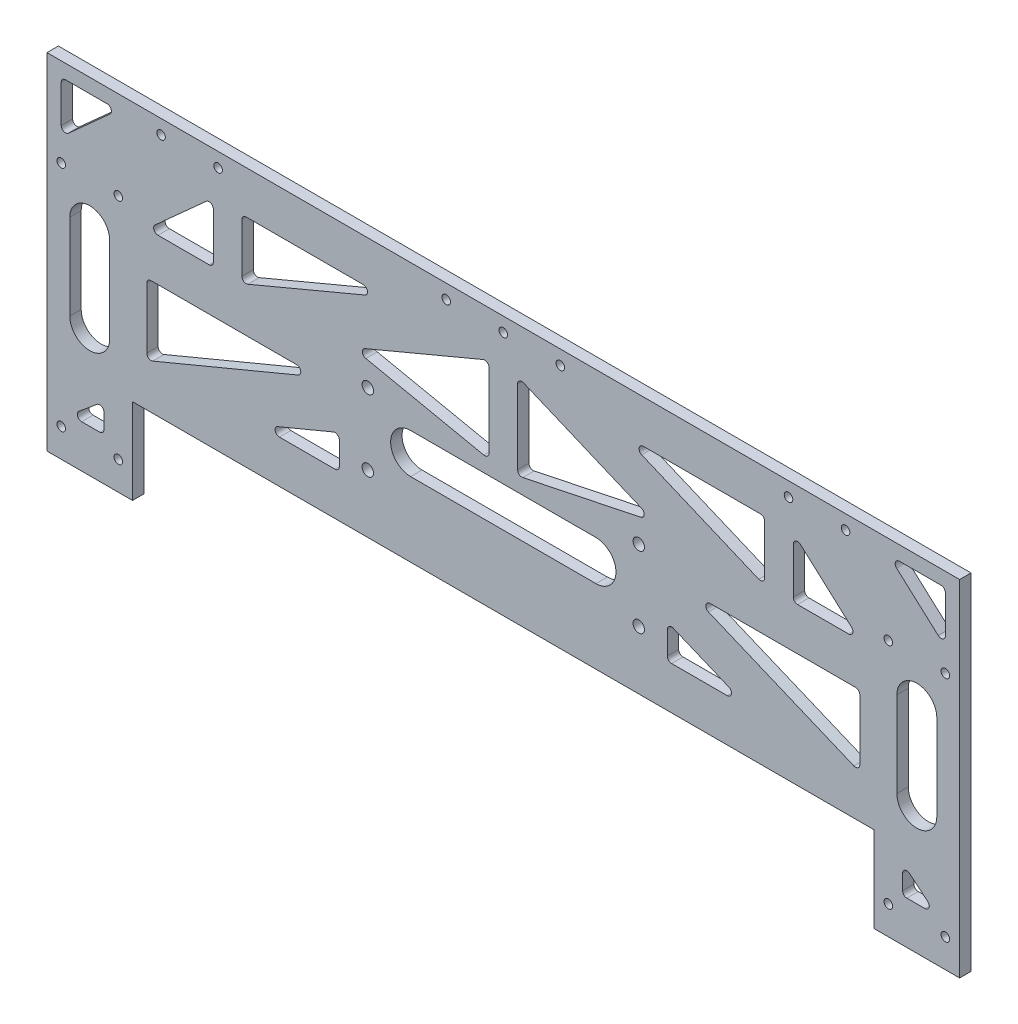
SolidWorks part; units mm, degrees
material "Thornel Mat VMA"
ref_plane "前视基准面" through (0, 0, 0) normal (0, 0, 1) x (1, 0, 0)
ref_plane "上视基准面" through (0, 0, 0) normal (0, 1, 0) x (1, 0, 0)
ref_plane "右视基准面" through (0, 0, 0) normal (1, 0, 0) x (0, 0, -1)
sketch "草图1" plane through (0, 0, 0) normal (0, 0, 1) x (1, 0, 0)
  line L1 (0, 0) -> (320, 0)
  line L2 (0, 0) -> (0, 121)
  line L3 (0, 121) -> (320, 121)
  line L4 (320, 0) -> (320, 121)
  dimension "D1" = 320
  dimension "D2" = 121
extrude "凸台-拉伸1" add sketch "草图1" along normal blind 4
sketch "草图2" plane through (0, 0, 4) normal (0, 0, 1) x (1, 0, 0)
  line L0 (160, 121) -> (160, 0) construction
  line L1 (320, 121) -> (0, 121) construction
  line L2 (0, 0) -> (320, 0) construction
  line L3 (0, 121) -> (0, 0) construction
  line L4 (30, 0) -> (35, 0)
  line L5 (30, 0) -> (30, 30)
  line L6 (30, 30) -> (35, 30)
  line L7 (35, 0) -> (35, 30)
  line L8 (285, 0) -> (285, 30)
  line L9 (290, 30) -> (285, 30)
  line L10 (290, 0) -> (290, 30)
  line L11 (290, 0) -> (285, 0)
  dimension "D1" = 30
  dimension "D2" = 30
  dimension "D3" = 5
extrude "切除-拉伸1" cut sketch "草图2" against normal through all
sketch "草图3" plane through (0, 0, 4) normal (0, 0, 1) x (1, 0, 0)
  line L0 (40, 116) -> (60, 116) construction
  line L1 (160, 121) -> (160, 0) construction
  line L2 (320, 121) -> (0, 121) construction
  line L3 (35, 0) -> (285, 0) construction
  line L4 (140, 116) -> (160, 116) construction
  line L5 (0, 121) -> (0, 0) construction
  line L6 (280, 116) -> (260, 116) construction
  circle A0 centre (40, 116) radius 1.5
  circle A1 centre (60, 116) radius 1.5
  circle A2 centre (140, 116) radius 1.5
  circle A3 centre (160, 116) radius 1.5
  circle A4 centre (260, 116) radius 1.5
  circle A5 centre (280, 116) radius 1.5
  circle A6 centre (180, 116) radius 1.5
  dimension "D5" = 3
  dimension "D1" = 40
  dimension "D2" = 5
  dimension "D3" = 20
  dimension "D4" = 20
extrude "切除-拉伸2" cut sketch "草图3" against normal through all
sketch "草图4" plane through (0, 0, 4) normal (0, 0, 1) x (1, 0, 0)
  line L0 (160, 121) -> (160, 0) construction
  line L1 (5, 90) -> (25, 90) construction
  line L2 (5, 90) -> (5, 10) construction
  line L3 (5, 10) -> (25, 10) construction
  line L4 (25, 90) -> (25, 10) construction
  line L5 (320, 121) -> (0, 121) construction
  line L6 (35, 0) -> (285, 0) construction
  line L7 (0, 0) -> (30, 0) construction
  line L8 (0, 121) -> (0, 0) construction
  line L10 (295, 90) -> (295, 10) construction
  line L11 (315, 10) -> (295, 10) construction
  line L12 (315, 90) -> (315, 10) construction
  line L13 (315, 90) -> (295, 90) construction
  circle A0 centre (5, 90) radius 1.5
  circle A1 centre (25, 90) radius 1.5
  circle A2 centre (5, 10) radius 1.5
  circle A3 centre (25, 10) radius 1.5
  circle A4 centre (295, 10) radius 1.5
  circle A5 centre (315, 10) radius 1.5
  circle A6 centre (295, 90) radius 1.5
  circle A7 centre (315, 90) radius 1.5
  dimension "D5" = 3
  dimension "D1" = 10
  dimension "D2" = 80
  dimension "D3" = 5
  dimension "D4" = 20
extrude "切除-拉伸3" cut sketch "草图4" against normal through all
sketch "草图6" plane through (0, 0, 4) normal (0, 0, 1) x (1, 0, 0)
  line L0 (160, 121) -> (160, 0) construction
  line L1 (320, 121) -> (0, 121) construction
  line L2 (35, 0) -> (285, 0) construction
  line L3 (127.5, 63) -> (192.5, 63) construction
  line L4 (112.5, 50.5) -> (207.5, 50.5) construction
  line L5 (112.5, 50.5) -> (112.5, 75.5) construction
  line L6 (112.5, 75.5) -> (207.5, 75.5) construction
  line L7 (207.5, 50.5) -> (207.5, 75.5) construction
  line L8 (112.5, 50.5) -> (207.5, 75.5) construction
  line L9 (112.5, 75.5) -> (207.5, 50.5) construction
  line L10 (127.5, 70) -> (192.5, 70)
  line L11 (127.5, 56) -> (192.5, 56)
  circle A0 centre (112.5, 75.5) radius 2
  circle A1 centre (207.5, 75.5) radius 2
  circle A2 centre (207.5, 50.5) radius 2
  circle A3 centre (112.5, 50.5) radius 2
  arc A4 (127.5, 70) -> (127.5, 56) centre (127.5, 63) ccw
  arc A5 (192.5, 56) -> (192.5, 70) centre (192.5, 63) ccw
  point P6 (160, 63)
  point P17 (160, 63)
  dimension "D1" = 4
  dimension "D5" = 7
  dimension "D2" = 25
  dimension "D3" = 95
  dimension "D4" = 45.5
  dimension "D6" = 15
extrude "切除-拉伸5" cut sketch "草图6" against normal through all
sketch "草图5" plane through (0, 0, 4) normal (0, 0, 1) x (1, 0, 0)
  line L0 (5, 101.368) -> (5, 114.5)
  line L1 (6.5, 116) -> (21.0911, 116)
  line L2 (22.0945, 113.3851) -> (7.5034, 100.2531)
  line L3 (15, 75) -> (15, 45) construction
  line L4 (22, 75) -> (22, 45)
  line L5 (8, 75) -> (8, 45)
  line L6 (5, 90) -> (25, 90) construction
  line L7 (0, 121) -> (0, 0) construction
  line L8 (320, 121) -> (0, 121) construction
  line L9 (38.9089, 85) -> (56.8333, 85)
  line L10 (58.3333, 86.5) -> (58.3333, 102.632)
  line L11 (55.8299, 103.7469) -> (37.9055, 87.6149)
  line L12 (160, 121) -> (160, 0) construction
  line L13 (35, 0) -> (285, 0) construction
  line L14 (35, 68.5) -> (35, 47.25)
  line L15 (35, 0) -> (285, 0)
  line L16 (35, 0) -> (35, 30)
  line L17 (35, 30) -> (285, 30)
  line L18 (285, 0) -> (285, 30)
  line L19 (37.0769, 45.8654) -> (88.0769, 67.1154)
  line L20 (87.5, 70) -> (36.5, 70)
  line L21 (81.5, 45) -> (101, 45)
  line L22 (102.5, 46.5) -> (102.5, 54.625)
  line L23 (100.4231, 56.0096) -> (80.9231, 47.8846)
  line L24 (68.3333, 87.2569) -> (68.3333, 104.5)
  line L25 (69.8333, 106) -> (110.8883, 106)
  line L26 (111.4691, 103.117) -> (70.4142, 85.874)
  line L27 (111.7889, 84.0154) -> (153.1936, 75.3769)
  line L28 (155, 76.8453) -> (155, 102.8738)
  line L29 (152.9192, 104.2567) -> (111.5144, 86.8668)
  line L30 (315, 90) -> (295, 90) construction
  line L31 (167.0808, 104.2567) -> (208.4856, 86.8668)
  line L32 (165, 76.8453) -> (165, 102.8738)
  line L33 (208.2111, 84.0154) -> (166.8064, 75.3769)
  line L34 (208.5309, 103.117) -> (249.5858, 85.874)
  line L35 (250.1667, 106) -> (209.1117, 106)
  line L36 (251.6667, 87.2569) -> (251.6667, 104.5)
  line L37 (219.5769, 56.0096) -> (239.0769, 47.8846)
  line L38 (217.5, 46.5) -> (217.5, 54.625)
  line L39 (238.5, 45) -> (219, 45)
  line L40 (232.5, 70) -> (283.5, 70)
  line L41 (282.9231, 45.8654) -> (231.9231, 67.1154)
  line L42 (285, 68.5) -> (285, 47.25)
  line L43 (264.1701, 103.7469) -> (282.0945, 87.6149)
  line L44 (261.6667, 86.5) -> (261.6667, 102.632)
  line L45 (281.0911, 85) -> (263.1667, 85)
  line L46 (297.9055, 113.3851) -> (312.4966, 100.2531)
  line L47 (313.5, 116) -> (298.9089, 116)
  line L48 (315, 101.368) -> (315, 114.5)
  line L49 (305, 75) -> (305, 45) construction
  line L50 (298, 75) -> (298, 45)
  line L51 (312, 75) -> (312, 45)
  line L52 (192.5, 70) -> (127.5, 70) construction
  line L53 (12.1431, 15) -> (18.5, 15)
  line L54 (20, 16.5) -> (20, 21.7974)
  line L55 (17.5397, 22.9498) -> (11.1828, 17.6523)
  line L56 (30, 30) -> (30, 0) construction
  line L57 (302.4603, 22.9498) -> (308.8172, 17.6523)
  line L58 (300, 16.5) -> (300, 21.7974)
  line L59 (307.8569, 15) -> (301.5, 15)
  arc A0 (22, 75) -> (8, 75) centre (15, 75) ccw
  arc A1 (8, 45) -> (22, 45) centre (15, 45) ccw
  arc A2 (155, 102.8738) -> (152.9192, 104.2567) centre (153.5, 102.8738) ccw
  circle A3 centre (5, 10) radius 1.5 construction
  arc A4 (21.0911, 116) -> (22.0945, 113.3851) centre (21.0911, 114.5) cw
  arc A5 (5, 101.368) -> (7.5034, 100.2531) centre (6.5, 101.368) ccw
  arc A6 (5, 114.5) -> (6.5, 116) centre (6.5, 114.5) cw
  arc A7 (56.8333, 85) -> (58.3333, 86.5) centre (56.8333, 86.5) ccw
  arc A8 (38.9089, 85) -> (37.9055, 87.6149) centre (38.9089, 86.5) cw
  arc A9 (58.3333, 102.632) -> (55.8299, 103.7469) centre (56.8333, 102.632) ccw
  arc A10 (88.0769, 67.1154) -> (87.5, 70) centre (87.5, 68.5) ccw
  arc A11 (35, 47.25) -> (37.0769, 45.8654) centre (36.5, 47.25) ccw
  arc A12 (35, 68.5) -> (36.5, 70) centre (36.5, 68.5) cw
  circle A13 centre (112.5, 75.5) radius 2 construction
  arc A14 (101, 45) -> (102.5, 46.5) centre (101, 46.5) ccw
  arc A15 (81.5, 45) -> (80.9231, 47.8846) centre (81.5, 46.5) cw
  arc A16 (102.5, 54.625) -> (100.4231, 56.0096) centre (101, 54.625) ccw
  arc A17 (153.1936, 75.3769) -> (155, 76.8453) centre (153.5, 76.8453) ccw
  arc A18 (111.7889, 84.0154) -> (111.5144, 86.8668) centre (112.0953, 85.4838) cw
  arc A19 (68.3333, 87.2569) -> (70.4142, 85.874) centre (69.8333, 87.2569) ccw
  arc A20 (68.3333, 104.5) -> (69.8333, 106) centre (69.8333, 104.5) cw
  arc A21 (110.8883, 106) -> (111.4691, 103.117) centre (110.8883, 104.5) cw
  arc A22 (209.1117, 106) -> (208.5309, 103.117) centre (209.1117, 104.5) ccw
  arc A23 (251.6667, 104.5) -> (250.1667, 106) centre (250.1667, 104.5) ccw
  arc A24 (251.6667, 87.2569) -> (249.5858, 85.874) centre (250.1667, 87.2569) cw
  arc A25 (208.2111, 84.0154) -> (208.4856, 86.8668) centre (207.9047, 85.4838) ccw
  arc A26 (166.8064, 75.3769) -> (165, 76.8453) centre (166.5, 76.8453) cw
  arc A27 (217.5, 54.625) -> (219.5769, 56.0096) centre (219, 54.625) cw
  arc A28 (238.5, 45) -> (239.0769, 47.8846) centre (238.5, 46.5) ccw
  arc A29 (219, 45) -> (217.5, 46.5) centre (219, 46.5) cw
  arc A30 (285, 68.5) -> (283.5, 70) centre (283.5, 68.5) ccw
  arc A31 (285, 47.25) -> (282.9231, 45.8654) centre (283.5, 47.25) cw
  arc A32 (231.9231, 67.1154) -> (232.5, 70) centre (232.5, 68.5) cw
  arc A33 (261.6667, 102.632) -> (264.1701, 103.7469) centre (263.1667, 102.632) cw
  arc A34 (281.0911, 85) -> (282.0945, 87.6149) centre (281.0911, 86.5) ccw
  arc A35 (263.1667, 85) -> (261.6667, 86.5) centre (263.1667, 86.5) cw
  arc A36 (315, 114.5) -> (313.5, 116) centre (313.5, 114.5) ccw
  arc A37 (315, 101.368) -> (312.4966, 100.2531) centre (313.5, 101.368) cw
  arc A38 (298.9089, 116) -> (297.9055, 113.3851) centre (298.9089, 114.5) ccw
  arc A39 (165, 102.8738) -> (167.0808, 104.2567) centre (166.5, 102.8738) cw
  arc A40 (298, 75) -> (312, 75) centre (305, 75) cw
  arc A41 (312, 45) -> (298, 45) centre (305, 45) cw
  arc A42 (18.5, 15) -> (20, 16.5) centre (18.5, 16.5) ccw
  arc A43 (12.1431, 15) -> (11.1828, 17.6523) centre (12.1431, 16.5) cw
  arc A44 (20, 21.7974) -> (17.5397, 22.9498) centre (18.5, 21.7974) ccw
  arc A45 (300, 21.7974) -> (302.4603, 22.9498) centre (301.5, 21.7974) cw
  arc A46 (307.8569, 15) -> (308.8172, 17.6523) centre (307.8569, 16.5) ccw
  arc A47 (301.5, 15) -> (300, 16.5) centre (301.5, 16.5) cw
  point P5 (15, 60)
  point P12 (15, 90)
  point P23 (25, 116)
  point P26 (5, 98)
  point P29 (5, 116)
  point P40 (35, 85)
  point P43 (58.3333, 106)
  point P56 (95, 70)
  point P59 (35, 45)
  point P62 (35, 70)
  point P84 (155, 105.1307)
  point P87 (155, 75)
  point P90 (107.0698, 85)
  point P93 (68.3333, 85)
  point P96 (68.3333, 106)
  point P99 (118.3333, 106)
  point P156 (201.6667, 106)
  point P157 (251.6667, 106)
  point P158 (251.6667, 85)
  point P159 (212.9302, 85)
  point P160 (165, 75)
  point P161 (165, 105.1307)
  point P162 (285, 70)
  point P163 (285, 45)
  point P164 (225, 70)
  point P165 (261.6667, 106)
  point P166 (285, 85)
  point P167 (315, 116)
  point P168 (315, 98)
  point P169 (295, 116)
  point P172 (305, 60)
  point P186 (20, 15)
  point P189 (8, 15)
  point P192 (20, 25)
  point P202 (300, 25)
  point P203 (312, 15)
  point P204 (300, 15)
  dimension "D1" = 7
  dimension "D8" = 1.5
  dimension "D12" = 1.5
  dimension "D16" = 1.5
  dimension "D20" = 1.5
  dimension "D27" = 1.5
  dimension "D32" = 1.5
  dimension "D2" = 15
  dimension "D3" = 35
  dimension "D4" = 5
  dimension "D5" = 5
  dimension "D6" = 20
  dimension "D7" = 18
  dimension "D9" = 5
  dimension "D10" = 10
  dimension "D11" = 10
  dimension "D13" = 15
  dimension "D14" = 15
  dimension "D15" = 60
  dimension "D17" = 15
  dimension "D18" = 10
  dimension "D19" = 15
  dimension "D21" = 15
  dimension "D22" = 10
  dimension "D23" = 50
  dimension "D24" = 15
  dimension "D25" = 10
  dimension "D26" = 5
  dimension "D28" = 10
  dimension "D29" = 8
  dimension "D30" = 5
  dimension "D31" = 10
extrude "切除-拉伸4" cut sketch "草图5" against normal through all
